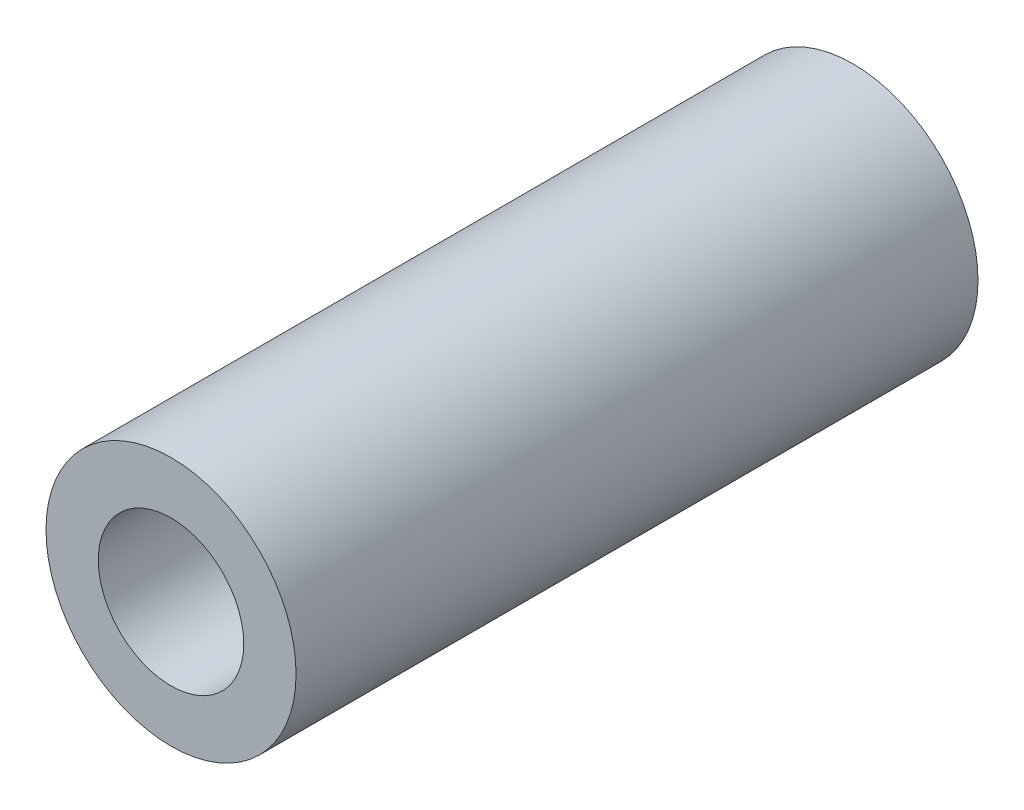
SolidWorks part; units mm, degrees
ref_plane "Front Plane" through (0, 0, 0) normal (0, 0, 1) x (1, 0, 0)
ref_plane "Top Plane" through (0, 0, 0) normal (0, 1, 0) x (1, 0, 0)
ref_plane "Right Plane" through (0, 0, 0) normal (1, 0, 0) x (0, 0, -1)
sketch "草圖1" plane through (0, 0, 0) normal (0, 0, 1) x (1, 0, 0)
  circle A0 centre (0, 0) radius 2.75
  circle A1 centre (0, 0) radius 1.6
extrude "填料-伸長1" add sketch "草圖1" along normal blind 15
